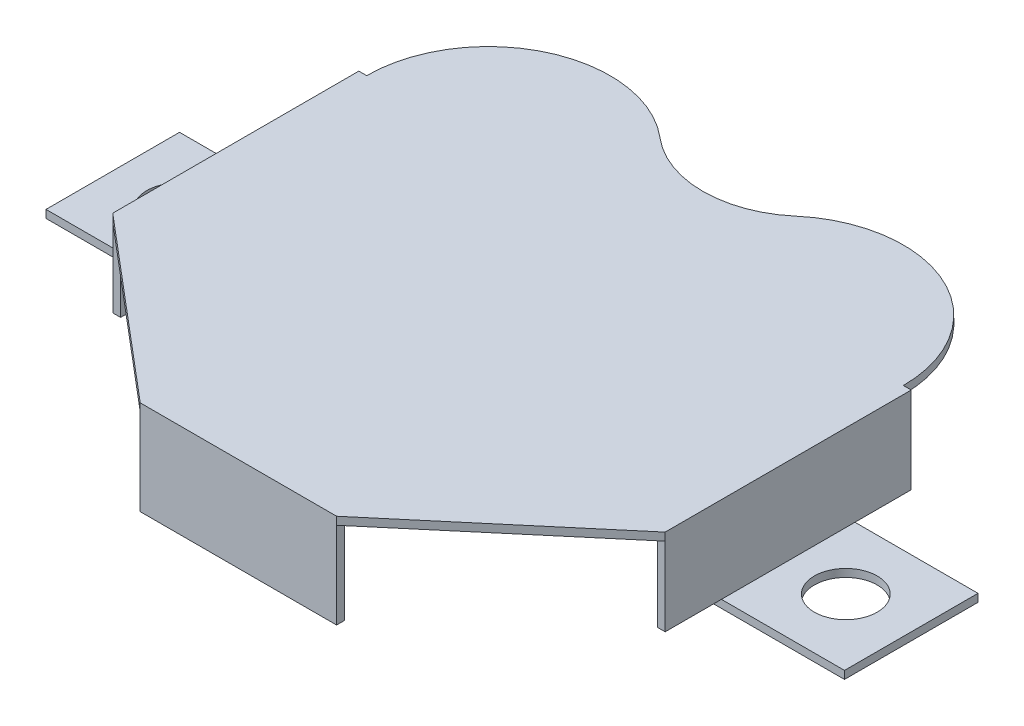
SolidWorks part; units mm, degrees
ref_plane "Front Plane" through (0, 0, 0) normal (0, 0, 1) x (1, 0, 0)
ref_plane "Top Plane" through (0, 0, 0) normal (0, 1, 0) x (1, 0, 0)
ref_plane "Right Plane" through (0, 0, 0) normal (1, 0, 0) x (0, 0, -1)
sketch "Sketch1" plane through (0, 0, 0) normal (0, 1, 0) x (1, 0, 0)
  line L0 (-12.75, 0) -> (0, 0) construction
  line L1 (-15.25, 2.55) -> (-10.25, 2.55)
  line L2 (-15.25, 2.55) -> (-15.25, -2.55)
  line L3 (-15.25, -2.55) -> (-10.25, -2.55)
  line L4 (-10.25, 2.55) -> (-10.25, -2.55)
  line L5 (10.25, 2.55) -> (15.25, 2.55)
  line L6 (10.25, 2.55) -> (10.25, -2.55)
  line L7 (10.25, -2.55) -> (15.25, -2.55)
  line L8 (15.25, 2.55) -> (15.25, -2.55)
  line L9 (0, 0) -> (12.75, 0) construction
  line L11 (-3.75, -10.15) -> (3.75, -10.15)
  line L12 (-3.75, -10.15) -> (-3.75, -10.45)
  line L13 (-3.75, -10.45) -> (3.75, -10.45)
  line L14 (3.75, -10.15) -> (3.75, -10.45)
  circle A0 centre (-12.75, 0) radius 1.2
  circle A1 centre (12.75, 0) radius 1.2
  point P13 (15.25, 0)
  point P14 (0, -10.15)
  point P18 (-12.75, 2.55)
  point P20 (12.75, 2.55)
  dimension "D1" = 2.4
  dimension "D2" = 5.1
  dimension "D3" = 30.5
  dimension "D4" = 5
  dimension "D5" = 0.3
  dimension "D6" = 7.9
  dimension "D7" = 7.5
extrude "Boss-Extrude1" add sketch "Sketch1" along normal blind 0.3
sketch "Sketch2" plane through (0, 0.3, 0) normal (0, 1, 0) x (1, 0, 0)
  line L0 (-10.25, -2.55) -> (-10.25, 2.55) construction
  line L1 (-10.55, 4.7) -> (-10.25, 4.7)
  line L2 (-10.55, 4.7) -> (-10.55, -4.7)
  line L3 (-10.55, -4.7) -> (-10.25, -4.7)
  line L4 (-10.25, 4.7) -> (-10.25, -4.7)
  line L5 (10.25, 4.7) -> (10.55, 4.7)
  line L6 (10.25, 4.7) -> (10.25, -4.7)
  line L7 (10.25, -4.7) -> (10.55, -4.7)
  line L8 (10.55, 4.7) -> (10.55, -4.7)
  line L9 (3.75, -10.15) -> (-3.75, -10.15)
  line L10 (3.75, -10.15) -> (3.75, -10.45)
  line L11 (3.75, -10.45) -> (-3.75, -10.45)
  line L12 (-3.75, -10.15) -> (-3.75, -10.45)
  line L13 (10.25, 2.55) -> (10.25, -2.55) construction
  point P18 (-10.25, 0)
  point P19 (10.25, 0)
  point P21 (-10.019, 4.7)
  point P22 (10.2568, 4.7)
  point P23 (-10.5597, 4.7)
  point P24 (10.4416, 4.7)
  dimension "D1" = 0.3
  dimension "D2" = 9.4
extrude "Boss-Extrude2" add sketch "Sketch2" along normal blind 3
sketch "Sketch3" plane through (0, 3.3, 0) normal (0, 1, 0) x (1, 0, 0)
  line L0 (-3.75, -10.45) -> (-10.55, -4.7)
  line L1 (3.75, -10.45) -> (10.55, -4.7)
  line L2 (10.25, 4.7) -> (10.25, -4.7) construction
  line L3 (-10.25, -4.7) -> (-10.25, 4.7) construction
  line L5 (-10.55, 9.35) -> (10.55, 9.35) construction
  line L7 (-3.75, -10.45) -> (3.75, -10.45) construction
  line L8 (-10.25, 4.7) -> (-10.55, 4.7)
  line L9 (-10.55, 4.7) -> (-10.55, -4.7)
  line L10 (10.25, 4.7) -> (10.55, 4.7)
  line L11 (10.55, 4.7) -> (10.55, -4.7)
  line L12 (-3.75, -10.45) -> (3.75, -10.45)
  arc A0 (-2.5876, 8.2423) -> (2.5876, 8.2423) centre (0, 11.2849) ccw
  arc A1 (-10.25, 4.7) -> (-2.5876, 8.2423) centre (-5.6, 4.7) cw
  arc A2 (10.25, 4.7) -> (2.5876, 8.2423) centre (5.6, 4.7) ccw
  dimension "D1" = 19.8
extrude "Boss-Extrude3" add sketch "Sketch3" along normal blind 0.3 contours L12 L1 L11 L10 A2 A0 A1 L8 L9 L0
